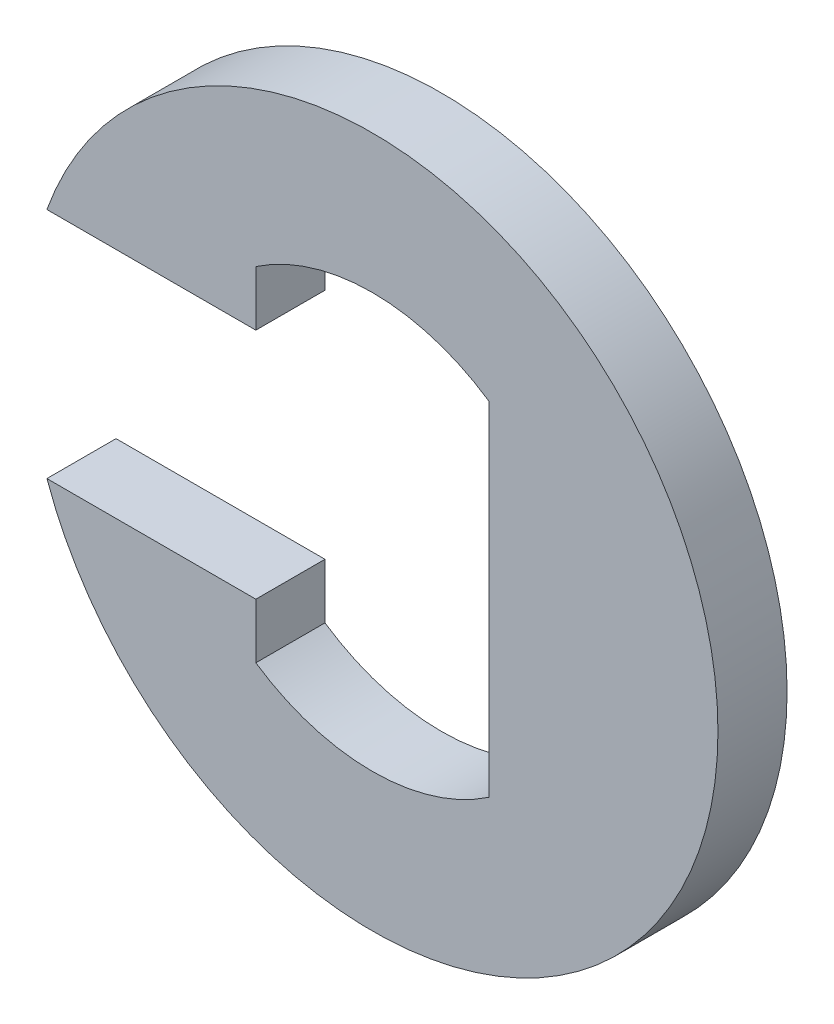
SolidWorks part; units mm, degrees
ref_plane "Piano frontale" through (0, 0, 0) normal (0, 0, 1) x (1, 0, 0)
ref_plane "Piano superiore" through (0, 0, 0) normal (0, 1, 0) x (1, 0, 0)
ref_plane "Piano destro" through (0, 0, 0) normal (1, 0, 0) x (0, 0, -1)
sketch "Schizzo1" plane through (0, 0, 0) normal (0, 0, 1) x (1, 0, 0)
  circle A0 centre (0, 0) radius 10
extrude "Estrusione-Estrusione1" add sketch "Schizzo1" along normal mid plane 2
sketch "Schizzo2" plane through (0, 0, 1) normal (0, 0, 1) x (1, 0, 0)
  line L0 (-3.37, 4.9642) -> (-3.37, -4.9642)
  line L1 (3.37, 4.9642) -> (3.37, -4.9642)
  line L2 (-11.1724, 3.37) -> (-3.37, 3.37)
  line L3 (-3.37, -3.37) -> (-11.1724, -3.37)
  line L4 (-11.1724, 3.37) -> (-11.1724, -3.37)
  line L5 (-3.37, 3.37) -> (-3.37, -3.37)
  arc A0 (3.37, 4.9642) -> (-3.37, 4.9642) centre (0, 0) ccw
  arc A1 (-3.37, -4.9642) -> (3.37, -4.9642) centre (0, 0) ccw
  circle M4 centre (0, 0) radius 10
  dimension "D1" = 3.37
  dimension "D2" = 3.37
  dimension "D3" = 6.74
extrude "Taglio-Estrusione1" cut sketch "Schizzo2" against normal through all contours L3 L0 L2 M4 | L0 A1 L1 A0
